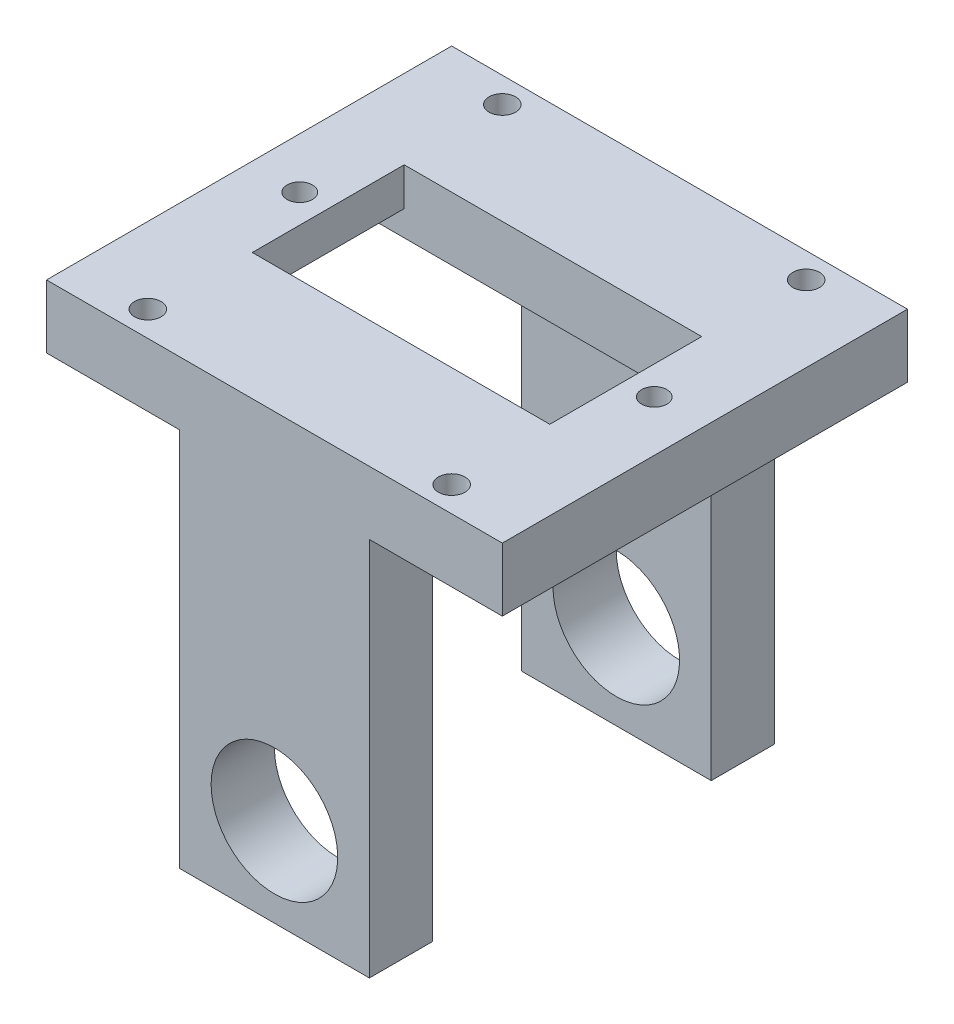
SolidWorks part; units mm, degrees
ref_plane "前视基准面" through (0, 0, 0) normal (0, 0, 1) x (1, 0, 0)
ref_plane "上视基准面" through (0, 0, 0) normal (0, 1, 0) x (1, 0, 0)
ref_plane "右视基准面" through (0, 0, 0) normal (1, 0, 0) x (0, 0, -1)
sketch "草图1" plane through (0, 0, 0) normal (0, 1, 0) x (1, 0, 0)
  line L1 (-18, 16) -> (18, 16)
  line L2 (-18, 16) -> (-18, -16)
  line L3 (-18, -16) -> (18, -16)
  line L4 (18, 16) -> (18, -16)
  line L5 (-18, 16) -> (18, -16) construction
  line L6 (-18, -16) -> (18, 16) construction
  point P0 (0, 0)
  dimension "D1" = 32
  dimension "D2" = 36
extrude "凸台-拉伸1" add sketch "草图1" along normal blind 5
sketch "草图4" plane through (0, 0, 0) normal (0, -1, 0) x (1, 0, 0)
  line L1 (-16.5, 6) -> (16.5, 6)
  line L2 (-16.5, 6) -> (-16.5, -6)
  line L3 (-16.5, -6) -> (16.5, -6)
  line L4 (16.5, 6) -> (16.5, -6)
  line L5 (-16.5, 6) -> (16.5, -6) construction
  line L6 (-16.5, -6) -> (16.5, 6) construction
  point P0 (0, 0)
  dimension "D1" = 33
  dimension "D2" = 12
extrude "切除-拉伸2" cut sketch "草图4" against normal blind 2
sketch "草图8" plane through (0, 2, 0) normal (0, -1, 0) x (1, 0, 0)
  line L0 (0, -1000) -> (0, 49000) construction
  circle A0 centre (14, 0) radius 1
  circle A1 centre (-14, 0) radius 1
  dimension "D1" = 28
  dimension "D2" = 2
extrude "切除-拉伸6" cut sketch "草图8" against normal blind 3
sketch "草图5" plane through (0, 2, 0) normal (0, -1, 0) x (1, 0, 0)
  line L0 (16.5, 6) -> (-16.5, 6) construction
  line L1 (-11.75, -6) -> (11.75, -6)
  line L2 (-11.75, -6) -> (-11.75, 6)
  line L3 (-11.75, 6) -> (11.75, 6)
  line L4 (11.75, -6) -> (11.75, 6)
  line L5 (-11.75, -6) -> (11.75, 6) construction
  line L6 (-11.75, 6) -> (11.75, -6) construction
  point P0 (0, 0)
  dimension "D1" = 23.5
extrude "切除-拉伸3" cut sketch "草图5" against normal up to surface (3 mm away) and the other way through all up to face at (-14, 5, -1)
sketch "草图11" plane through (0, 0, 0) normal (0, -1, 0) x (1, 0, 0)
  line L0 (0, 15) -> (0, 3.8777) construction
  line L2 (18, 0) -> (9.4315, 0) construction
  line L4 (-18, 16) -> (18, 16) construction
  line L5 (-7.5, 16) -> (7.5, 16)
  line L6 (-7.5, 16) -> (-7.5, 11)
  line L7 (-7.5, 11) -> (7.5, 11)
  line L8 (7.5, 16) -> (7.5, 11)
  line L9 (-7.5, 16) -> (7.5, 11) construction
  line L10 (-7.5, 11) -> (7.5, 16) construction
  line L11 (-7.5, -11) -> (7.5, -11)
  line L12 (7.5, -16) -> (7.5, -11)
  line L13 (-7.5, -16) -> (7.5, -16)
  line L14 (-7.5, -16) -> (-7.5, -11)
  point P2 (0, 13.5)
  dimension "D1" = 15
  dimension "D2" = 5
extrude "凸台-拉伸3" add sketch "草图11" along normal blind 30
sketch "草图12" plane through (0, 0, -16) normal (0, 0, -1) x (-1, 0, 0)
  line L0 (0, -30) -> (0, -16.5748) construction
  line L1 (7.5, -30) -> (-7.5, -30) construction
  circle A0 centre (0, -23) radius 5
  dimension "D1" = 10
  dimension "D2" = 7
extrude "切除-拉伸8" cut sketch "草图12" against normal up to surface (32 mm away) up to face at (0, -6.25, 16)
sketch "草图13" plane through (0, 0, 0) normal (0, -1, 0) x (1, 0, 0)
  line L0 (0, 16) -> (0, -16) construction
  line L1 (7.5, 16) -> (-7.5, 16) construction
  line L2 (-7.5, -16) -> (7.5, -16) construction
  line L3 (18, 0) -> (-18, 0) construction
  line L4 (18, 16) -> (18, -16) construction
  line L5 (-18, -16) -> (-18, 16) construction
  line L6 (-18, 16) -> (-7.5, 16) construction
  circle A0 centre (-12, 14) radius 1.05
  circle A1 centre (12, 14) radius 1.05
  circle A2 centre (12, -14) radius 1.05
  circle A3 centre (-12, -14) radius 1.05
  dimension "D1" = 2.1
  dimension "D2" = 2
  dimension "D3" = 12
extrude "切除-拉伸9" cut sketch "草图13" against normal up to next
